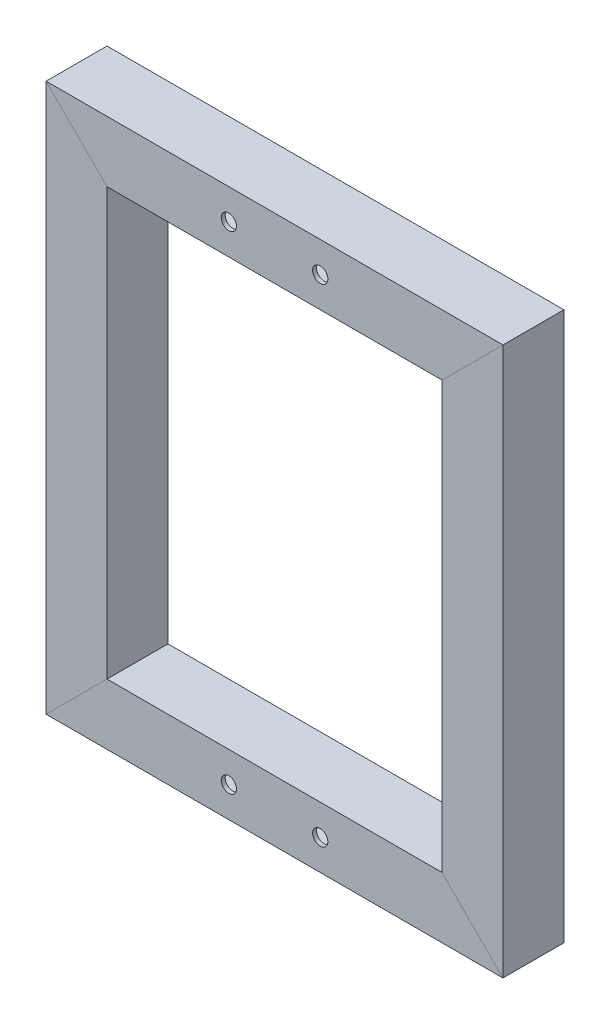
SolidWorks part; units mm, degrees
ref_plane "Front Plane" through (0, 0, 0) normal (0, 0, 1) x (1, 0, 0)
ref_plane "Top Plane" through (0, 0, 0) normal (0, 1, 0) x (1, 0, 0)
ref_plane "Right Plane" through (0, 0, 0) normal (1, 0, 0) x (0, 0, -1)
sketch "Sketch1" plane through (0, 0, 0) normal (0, 0, 1) x (1, 0, 0)
  line L0 (-121.8407, -134.9384) -> (-121.8407, 180.4636) construction
  line L1 (-217.0907, 144.099) -> (-26.5907, 144.099)
  line L2 (-217.0907, 144.099) -> (-217.0907, -84.501)
  line L3 (-217.0907, -84.501) -> (-26.5907, -84.501)
  line L4 (-26.5907, 144.099) -> (-26.5907, -84.501)
  line L5 (-217.0907, 144.099) -> (-26.5907, -84.501) construction
  line L6 (-217.0907, -84.501) -> (-26.5907, 144.099) construction
  point P0 (-121.8407, 29.799)
  dimension "D1" = 190.5
  dimension "D2" = 228.6
other "Structural Member1"
ref_plane "Plane1" through (-217.0907, 131.399, 12.7) normal (1, 0, 0) x (0, 1, 0)
sketch "Sketch11" plane through (-217.0907, 131.399, 12.7) normal (1, 0, 0) x (0, 1, 0)
  line L0 (-11.049, -11.049) -> (-11.049, 11.049)
  line L1 (11.049, 11.049) -> (-11.049, 11.049)
  line L2 (11.049, 11.049) -> (11.049, -11.049)
  line L3 (-11.049, -11.049) -> (11.049, -11.049)
  line L4 (-12.7, -12.7) -> (12.7, -12.7)
  line L5 (-12.7, -12.7) -> (-12.7, 12.7)
  line L6 (12.7, 12.7) -> (-12.7, 12.7)
  line L7 (12.7, 12.7) -> (12.7, -12.7)
  line L8 (0, -11.049) -> (0, -12.7) construction
  line L9 (0, -11.049) -> (0, 11.049) construction
  line L10 (0, 11.049) -> (0, 12.7) construction
  line L11 (12.7, 0) -> (11.049, 0) construction
  line L12 (11.049, 0) -> (-11.049, 0) construction
  line L13 (-11.049, 0) -> (-12.7, 0) construction
  point P14 (0, 0)
  dimension "Thickness" = 1.651
  dimension "V_leg" = 25.4
  dimension "H_leg" = 25.4
sketch "Sketch13" plane through (0, 0, 0) normal (0, 0, -1) x (-1, 0, 0)
  line L1 (121.8407, -134.9384) -> (121.8407, 180.4636) construction
  line L2 (121.8407, 29.799) -> (121.8407, 173.9562) construction
  line L5 (51.9907, 118.699) -> (191.6907, 118.699) construction
  circle A0 centre (102.7907, 131.399) radius 3.175
  circle A1 centre (140.8907, 131.399) radius 3.175
  dimension "D1" = 38.1
  dimension "D2" = 12.7
  dimension "D3" = 12.7
extrude "Cut-Extrude1" cut sketch "Sketch13" against normal through all contours A0 | A1
sketch "Sketch14" plane through (0, 0, 0) normal (0, 0, -1) x (-1, 0, 0)
  line L0 (121.8407, -55.5841) -> (121.8407, -111.7913) construction
  line L2 (121.8407, -134.9384) -> (121.8407, 180.4636) construction
  line L4 (191.6907, -59.101) -> (51.9907, -59.101) construction
  circle A0 centre (140.8907, -71.801) radius 3.175
  circle A2 centre (102.7907, -71.801) radius 3.175
  dimension "D1" = 38.1
  dimension "D2" = 12.7
  dimension "D3" = 12.7
extrude "Cut-Extrude2" cut sketch "Sketch14" against normal through all contours A0 | A2
